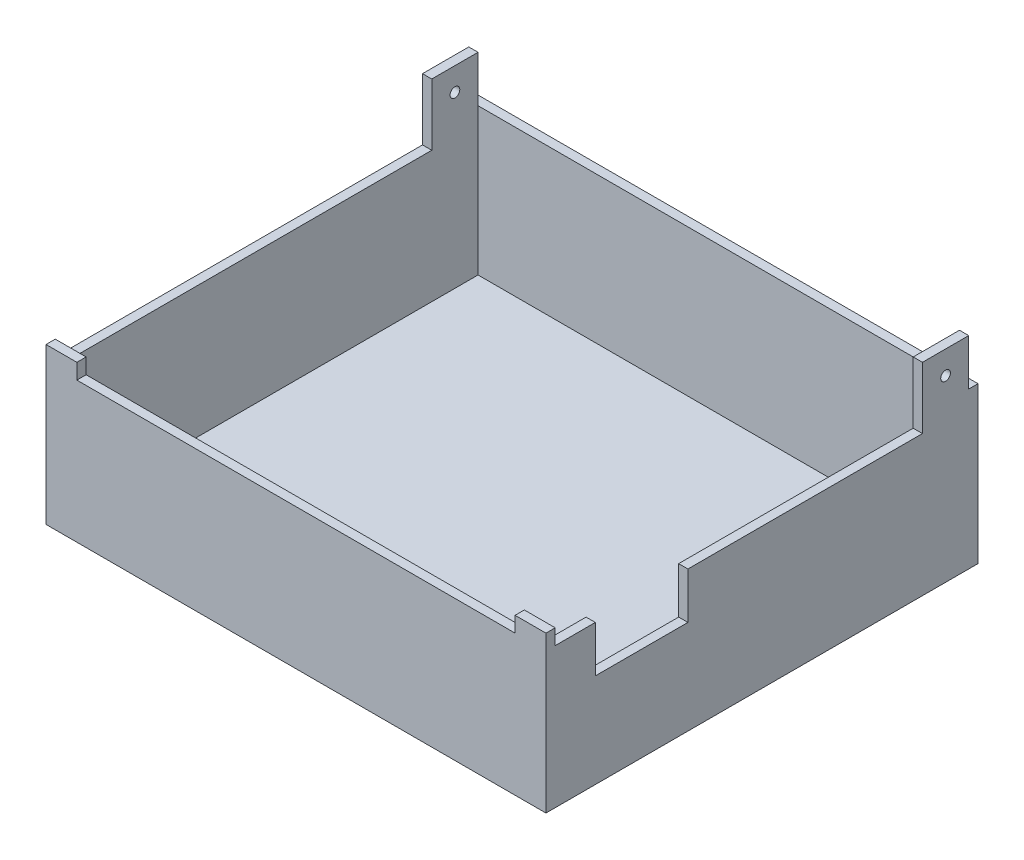
SolidWorks part; units mm, degrees
other "Markup1"
sketch "Sketch7" plane through (81, 65.5, 70) normal (0.9982, 0.0529, 0.0283) x (0.0279, 0.0092, -0.9996)
ref_plane "Front Plane" through (0, 0, 0) normal (0, 0, 1) x (1, 0, 0)
ref_plane "Top Plane" through (0, 0, 0) normal (0, 1, 0) x (1, 0, 0)
ref_plane "Right Plane" through (0, 0, 0) normal (1, 0, 0) x (0, 0, -1)
sketch "Sketch1" plane through (0, 0, 0) normal (0, 1, 0) x (1, 0, 0)
  line L1 (81, 70) -> (-81, 70)
  line L2 (81, 70) -> (81, -70)
  line L3 (81, -70) -> (-81, -70)
  line L4 (-81, 70) -> (-81, -70)
  line L5 (81, 70) -> (-81, -70) construction
  line L6 (81, -70) -> (-81, 70) construction
  point P0 (0, 0)
  dimension "D1" = 162
  dimension "D2" = 140
extrude "Boss-Extrude2" add sketch "Sketch1" along normal blind 3
sketch "Sketch2" plane through (0, 3, 0) normal (0, 1, 0) x (1, 0, 0)
  line L0 (81, -70) -> (81, 70) construction
  line L1 (-78, 67) -> (78, 67)
  line L2 (-78, 67) -> (-78, -67)
  line L3 (-78, -67) -> (78, -67)
  line L4 (78, 67) -> (78, -67)
  line L5 (-78, 67) -> (78, -67) construction
  line L6 (-78, -67) -> (78, 67) construction
  line L7 (81, 70) -> (-81, 70) construction
  line L9 (-81, 70) -> (81, 70)
  line L10 (-81, 70) -> (-81, -70)
  line L11 (-81, -70) -> (81, -70)
  line L12 (81, 70) -> (81, -70)
  line L13 (-81, 70) -> (81, -70) construction
  line L14 (-81, -70) -> (81, 70) construction
  point P0 (0, 0)
  point P10 (0, 0)
  dimension "D1" = 3
  dimension "D2" = 3
extrude "Boss-Extrude3" add sketch "Sketch2" along normal blind 47.5
sketch "Sketch4" plane through (0, 50.5, 0) normal (0, 1, 0) x (1, 0, 0)
  line L0 (-81, 70) -> (-81, -70) construction
  line L1 (-78, 67) -> (-81, 67)
  line L2 (-78, 67) -> (-78, -67)
  line L3 (-78, -67) -> (-81, -67)
  line L4 (-81, 67) -> (-81, -67)
  line L5 (81, -70) -> (81, 70) construction
  line L6 (78, 67) -> (81, 67)
  line L7 (78, 67) -> (78, -67)
  line L8 (78, -67) -> (81, -67)
  line L9 (81, 67) -> (81, -67)
  dimension "D1" = 3
  dimension "D2" = 134
  dimension "D3" = 134
extrude "Boss-Extrude4" add sketch "Sketch4" along normal blind 15
sketch "Sketch5" plane through (81, 0, 0) normal (1, 0, 0) x (0, 0, -1)
  line L0 (67, 65.5) -> (67, 50.5) construction
  line L5 (52, 65.5) -> (-67, 65.5)
  line L6 (52, 65.5) -> (52, 45.5)
  line L7 (0, 0) -> (0, 65.5) construction
  line L8 (-67, 65.5) -> (67, 65.5) construction
  line L13 (52, 45.5) -> (-67, 45.5)
  line L18 (-67, 65.5) -> (-67, 45.5)
  circle A3 centre (59.5, 58) radius 1.575
  dimension "D4" = 7.5
  dimension "D2" = 20
  dimension "D3" = 7.5
  dimension "D1" = 15
extrude "Cut-Extrude3" cut sketch "Sketch5" against normal through all
sketch "Sketch9" plane through (0, 0, 70) normal (0, 0, 1) x (1, 0, 0)
  line L0 (-81, 50.5) -> (81, 50.5) construction
  line L1 (-71, 50.5) -> (71, 50.5)
  line L2 (-71, 50.5) -> (-71, 45.5)
  line L3 (-71, 45.5) -> (71, 45.5)
  line L4 (71, 50.5) -> (71, 45.5)
  line L5 (-81, 50.5) -> (-81, 0) construction
  line L6 (81, 50.5) -> (81, 0) construction
  dimension "D1" = 5
  dimension "D2" = 10
  dimension "D3" = 10
extrude "Cut-Extrude4" cut sketch "Sketch9" against normal up to next
sketch "Sketch10" plane through (81, 0, 0) normal (1, 0, 0) x (0, 0, -1)
  line L0 (-70, 50.5) -> (-70, 0) construction
  line L1 (-54, 45.5) -> (-24, 45.5)
  line L2 (-54, 45.5) -> (-54, 30.5)
  line L3 (-54, 30.5) -> (-24, 30.5)
  line L4 (-24, 45.5) -> (-24, 30.5)
  line L7 (-67, 45.5) -> (52, 45.5) construction
  point P7 (-24, 39.3897)
  dimension "D1" = 30
  dimension "D2" = 15
  dimension "D3" = 16
extrude "Cut-Extrude5" cut sketch "Sketch10" against normal up to next
